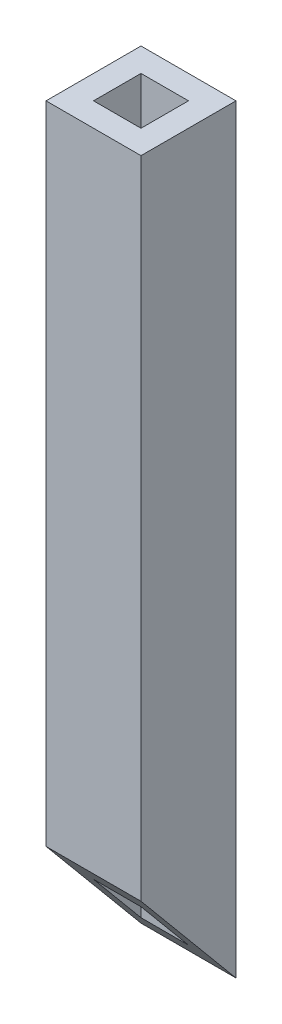
SolidWorks part; units mm, degrees
ref_plane "Front Plane" through (0, 0, 0) normal (0, 0, 1) x (1, 0, 0)
ref_plane "Top Plane" through (0, 0, 0) normal (0, 1, 0) x (1, 0, 0)
ref_plane "Right Plane" through (0, 0, 0) normal (1, 0, 0) x (0, 0, -1)
sketch "Sketch2" plane through (0, 0, 0) normal (0, 0, 1) x (1, 0, 0)
  line L1 (0, 0) -> (25.4, 0)
  line L2 (0, 0) -> (0, 203.2)
  line L3 (0, 203.2) -> (25.4, 203.2)
  line L4 (25.4, 0) -> (25.4, 203.2)
  dimension "D1" = 25.4
  dimension "D2" = 203.2
extrude "Boss-Extrude2" add sketch "Sketch2" along normal blind 25.4
sketch "Sketch3" plane through (0, 0, 0) normal (0, -1, 0) x (1, 0, 0)
  line L0 (0, 0) -> (25.4, 0) construction
  line L1 (19.05, 6.35) -> (6.35, 6.35)
  line L2 (19.05, 6.35) -> (19.05, 19.05)
  line L3 (19.05, 19.05) -> (6.35, 19.05)
  line L4 (6.35, 6.35) -> (6.35, 19.05)
  line L5 (0, 25.4) -> (0, 0) construction
  line L6 (0, 25.4) -> (25.4, 25.4) construction
  line L7 (25.4, 25.4) -> (25.4, 0) construction
  dimension "D1" = 6.35
  dimension "D2" = 6.35
  dimension "D3" = 6.35
  dimension "D4" = 6.35
extrude "Cut-Extrude1" cut sketch "Sketch3" against normal through all
sketch "Sketch4" plane through (25.4, 0, 0) normal (1, 0, 0) x (0, 0, -1)
  line L0 (0, 0) -> (-25.4, 30.48)
  line L1 (-25.4, 0) -> (-25.4, 203.2) construction
  line L2 (-25.4, 30.48) -> (-25.4, 0)
  line L3 (-25.4, 0) -> (0, 0) construction
  line L4 (-25.4, 0) -> (0, 0)
  dimension "D1" = 30.48
extrude "Cut-Extrude2" cut sketch "Sketch4" against normal through all
